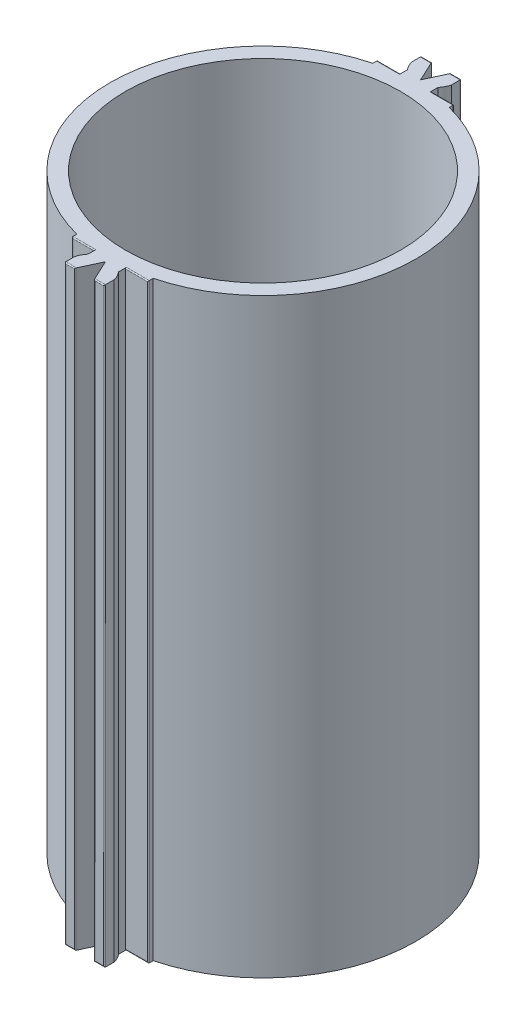
SolidWorks part; units mm, degrees
ref_plane "前视基准面" through (0, 0, 0) normal (0, 0, 1) x (1, 0, 0)
ref_plane "上视基准面" through (0, 0, 0) normal (0, 1, 0) x (1, 0, 0)
ref_plane "右视基准面" through (0, 0, 0) normal (1, 0, 0) x (0, 0, -1)
sketch "草图1" plane through (0, 0, 0) normal (0, 1, 0) x (1, 0, 0)
  circle A0 centre (0, 0) radius 15
  circle A1 centre (0, 0) radius 13.5
  dimension "D1" = 30
  dimension "D2" = 27
extrude "凸台-拉伸1" add sketch "草图1" along normal blind 58
sketch "草图10" plane through (0, 0, 0) normal (0, 1, 0) x (1, 0, 0)
  line L0 (0, 15) -> (3.75, 15)
  line L1 (3.75, 15) -> (3.75, 14.5237)
  line L2 (0, 0) -> (0, 15) construction
  arc A1 (3.75, 14.5237) -> (0, 15) centre (0, 0) ccw
  dimension "D1" = 30
  dimension "D2" = 3.75
extrude "凸台-拉伸2" add sketch "草图10" along normal blind 58
mirror "镜向1" about plane through (0, 0, 0) normal (1, 0, 0) of "凸台-拉伸2"
sketch "草图11" plane through (0, 0, 0) normal (0, 1, 0) x (1, 0, 0)
  line L0 (0, 15) -> (0, 17) construction
  line L1 (3.75, 15) -> (-3.75, 15) construction
  line L2 (0, 17) -> (0, 17.5) construction
  line L3 (-1.5, 15) -> (1.5, 15)
  line L4 (1.5, 15) -> (1.5, 15.6771)
  line L5 (0, 17.5) -> (1.95, 17.5) construction
  line L6 (1.95, 17.5) -> (1.95, 16.5556)
  line L7 (1.95, 17.5) -> (0.95, 17.5)
  line L8 (0.95, 17.5) -> (0, 15.4627)
  line L9 (-1.5, 15) -> (-1.5, 15.6771)
  line L10 (-1.95, 17.5) -> (-1.95, 16.5556)
  line L11 (-1.95, 17.5) -> (-0.95, 17.5)
  line L12 (-0.95, 17.5) -> (0, 15.4627)
  arc A0 (1.5, 15.6771) -> (1.95, 16.5556) centre (0, 17) ccw
  arc A1 (-1.5, 15.6771) -> (-1.95, 16.5556) centre (0, 17) cw
  dimension "D5" = 2
  dimension "D1" = 2
  dimension "D2" = 0.5
  dimension "D3" = 1.5
  dimension "D4" = 1.95
  dimension "D6" = 1
  dimension "D7" = 25
extrude "凸台-拉伸3" add sketch "草图11" along normal blind 58
fillet "圆角1" radius 0.1 14 edges at (-0.95, 29, -17.5) (-1.45, 58, -17.5) (-1.95, 29, -17.5) (-1.45, 0, -17.5) (1.95, 29, -17.5) (1.45, 58, -17.5) (0.95, 29, -17.5) (1.45, 0, -17.5) (3.75, 29, -15) (-3.75, 29, -15)
mirror "镜向2" about plane through (0, 0, 0) normal (0, 0, 1) of "圆角1", "凸台-拉伸3", "镜向1", "凸台-拉伸2"
